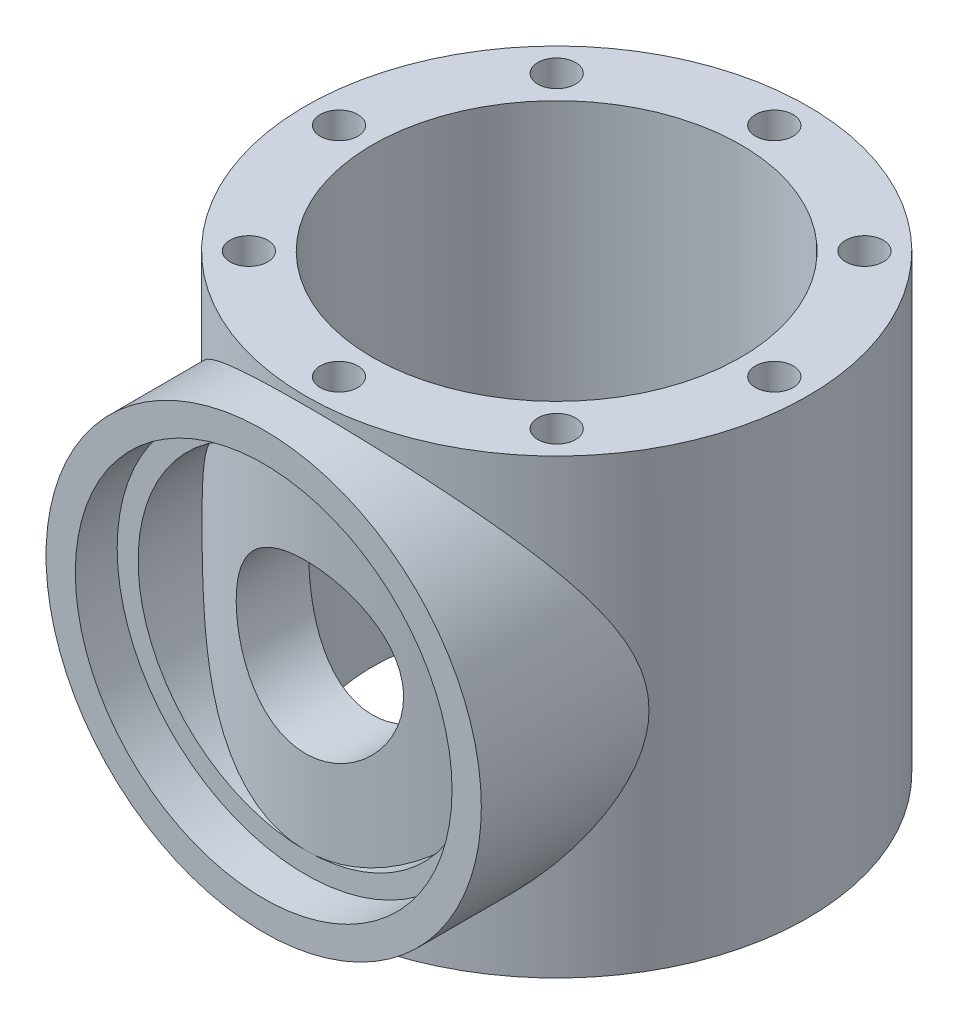
SolidWorks part; units mm, degrees
ref_plane "Спереди" through (0, 0, 0) normal (0, 0, 1) x (1, 0, 0)
ref_plane "Сверху" through (0, 0, 0) normal (0, 1, 0) x (1, 0, 0)
ref_plane "Справа" through (0, 0, 0) normal (1, 0, 0) x (0, 0, -1)
sketch "Эскиз1" plane through (0, 0, 0) normal (0, 1, 0) x (1, 0, 0)
  circle A0 centre (0, 0) radius 22
  circle A1 centre (0, 0) radius 30
  dimension "D1" = 44
  dimension "D2" = 60
extrude "Бобышка-Вытянуть1" add sketch "Эскиз1" along normal blind 54
sketch "Эскиз3" plane through (0, 54, 0) normal (0, 1, 0) x (1, 0, 0)
  line L0 (0, 30) -> (0, -30) construction
  circle A0 centre (0, 0) radius 26 construction
  circle A1 centre (0, 0) radius 30 construction
  circle A2 centre (0, 26) radius 2
  circle A3 centre (18.3848, 18.3848) radius 2
  circle A4 centre (26, 0) radius 2
  circle A5 centre (18.3848, -18.3848) radius 2
  circle A6 centre (0, -26) radius 2
  circle A7 centre (-18.3848, -18.3848) radius 2
  circle A8 centre (-26, 0) radius 2
  circle A9 centre (-18.3848, 18.3848) radius 2
  point P10 (0, 0)
  point P26 (0, 0)
  dimension "D1" = 8
hole_wizard "Отверстие с зазором M41" positions "Эскиз4" profile "Эскиз5" hole size "M4" standard "ISO"
sketch "Эскиз4" plane through (0, 54, 0) normal (0, 1, 0) x (1, 0, 0)
  point P0 (-18.3848, 18.3848)
  point P3 (0, 26)
  point P6 (18.3848, 18.3848)
  point P9 (26, 0)
  point P12 (18.3848, -18.3848)
  point P15 (0, -26)
  point P18 (-18.3848, -18.3848)
  point P21 (-26, 0)
sketch "Эскиз5" plane through (-18.3848, 54, -18.3848) normal (1, 0, 0) x (0, 0, 1)
  line L0 (0, 0) -> (0, 13.3519)
  line L1 (0, 13.3519) -> (2.25, 12)
  line L2 (2.25, 12) -> (2.25, 0)
  line L5 (2.25, 0) -> (0, 0)
  line L10 (0, 13.3519) -> (-2.25, 12) construction
  line L11 (0, -6.35) -> (0, 107.95) construction
  dimension "Диаметр отверстия" = 4.5
  dimension "Глубина отверстия" = 12
  dimension "Угол заточки сверла" = 118
ref_plane "Плоскость1" through (0, 27, 0) normal (0, 1, 0) x (1, 0, 0)
mirror "Зеркальное отражение1" about plane through (0, 27, 0) normal (0, 1, 0) of "Отверстие с зазором M41"
ref_plane "Плоскость2" through (0, 0, 0) normal (0, 0, 1) x (1, 0, 0)
ref_plane "Плоскость3" through (0, 0, 35) normal (0, 0, 1) x (1, 0, 0)
sketch "Эскиз6" plane through (0, 0, 35) normal (0, 0, 1) x (1, 0, 0)
  line L0 (0, 0) -> (0, 54) construction
  line L1 (0, 27) -> (39.3345, 27) construction
  line L2 (33, 27) -> (-33, 27) construction
  line L3 (39.3345, 27) -> (-33.9059, 27) construction
  circle A0 centre (0, 27) radius 20
sketch "Эскиз7" plane through (0, 0, 35) normal (0, 0, 1) x (1, 0, 0)
  line L0 (0, 0) -> (0, 54) construction
  line L1 (0, 54) -> (0, 27) construction
  line L2 (0, 27) -> (-37.0029, 27) construction
  line L3 (-37.0029, 27) -> (37.9953, 27) construction
  circle A0 centre (0, 27) radius 20
  circle A1 centre (0, 27) radius 26
  dimension "D1" = 52
  dimension "D2" = 40
extrude "Бобышка-Вытянуть2" add sketch "Эскиз7" against normal up to next
sketch "Эскиз9" plane through (0, 0, 35) normal (0, 0, 1) x (1, 0, 0)
  circle A0 centre (0, 27) radius 22.5
  dimension "D1" = 45
extrude "Вырез-Вытянуть3" cut sketch "Эскиз9" against normal blind 5
sketch "Эскиз10" plane through (0, 0, 30) normal (0, 0, 1) x (1, 0, 0)
  line L0 (0, 0) -> (0, 54) construction
  circle A1 centre (0, 27) radius 10
  dimension "D1" = 20
extrude "Вырез-Вытянуть4" cut sketch "Эскиз10" against normal blind 15 contours A1
